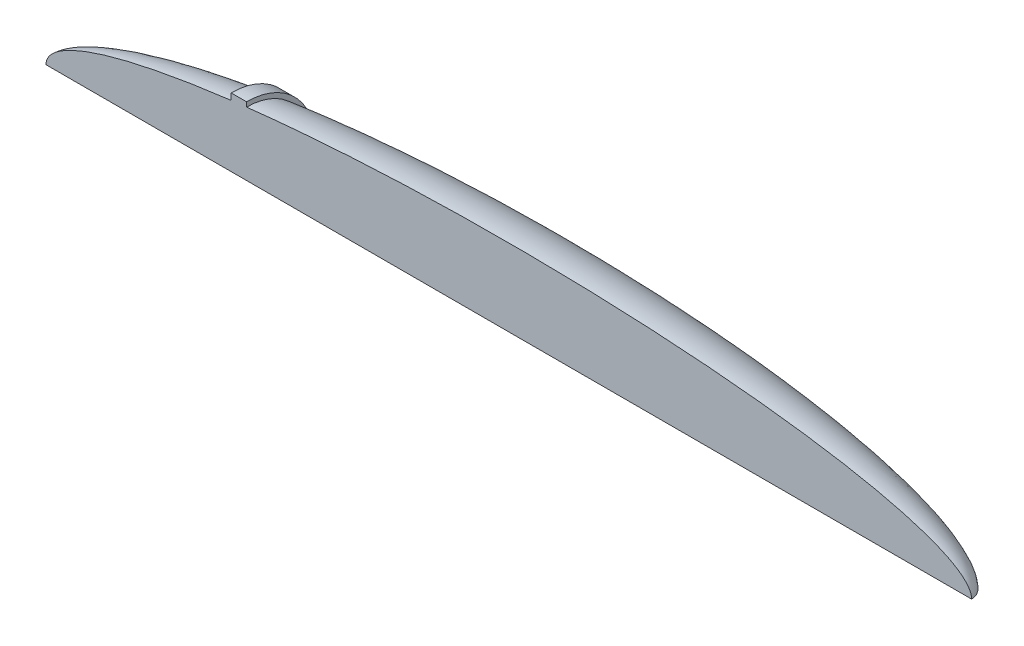
SolidWorks part; units mm, degrees
ref_plane "Front Plane" through (0, 0, 0) normal (0, 0, 1) x (1, 0, 0)
ref_plane "Top Plane" through (0, 0, 0) normal (0, 1, 0) x (1, 0, 0)
ref_plane "Right Plane" through (0, 0, 0) normal (1, 0, 0) x (0, 0, -1)
sketch "Sketch1" plane through (0, 0, 0) normal (0, 1, 0) x (1, 0, 0)
  line L0 (-1000, 0) -> (49000, 0) construction
  line L1 (-6000, 0) -> (6000, 0)
  line L4 (-3400, 883.9471) -> (-3400, 823.9471)
  line L6 (-3400, 883.9471) -> (-3600, 883.9471)
  line L7 (-3600, 883.9471) -> (-3600, 800)
  ellipse E0 centre (0, 0) end of major axis (6000, 0) minor radius 1000 (6000, 0) -> (-3400, 823.9471) ccw
  ellipse E1 centre (0, 0) end of major axis (6000, 0) minor radius 1000 (-3600, 800) -> (-6000, 0) ccw
  dimension "D1" = 6000
  dimension "D2" = 1000
  dimension "D3" = 60
  dimension "D4" = 200
  dimension "D5" = 2400
revolve "Revolve1" add sketch "Sketch1" angle 90 about L0
